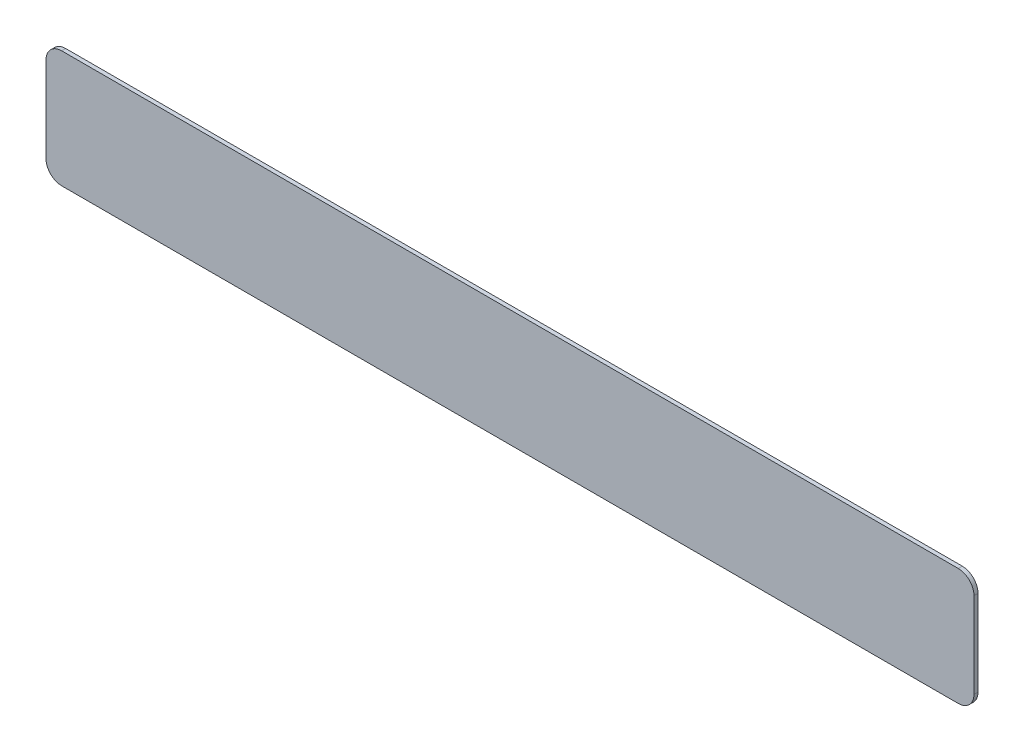
SolidWorks part; units mm, degrees
ref_plane "Front Plane" through (0, 0, 0) normal (0, 0, 1) x (1, 0, 0)
ref_plane "Top Plane" through (0, 0, 0) normal (0, 1, 0) x (1, 0, 0)
ref_plane "Right Plane" through (0, 0, 0) normal (1, 0, 0) x (0, 0, -1)
sketch "Sketch1" plane through (0, 0, 0) normal (0, 0, 1) x (1, 0, 0)
  line L1 (-35.65, 4.65) -> (35.65, 4.65)
  line L2 (-36.9, 3.4) -> (-36.9, -3.4)
  line L3 (-35.65, -4.65) -> (35.65, -4.65)
  line L4 (36.9, 3.4) -> (36.9, -3.4)
  line L5 (-36.9, 4.65) -> (36.9, -4.65) construction
  line L6 (-36.9, -4.65) -> (36.9, 4.65) construction
  arc A0 (-36.9, -3.4) -> (-35.65, -4.65) centre (-35.65, -3.4) ccw
  arc A1 (35.65, -4.65) -> (36.9, -3.4) centre (35.65, -3.4) ccw
  arc A2 (35.65, 4.65) -> (36.9, 3.4) centre (35.65, 3.4) cw
  arc A3 (-35.65, 4.65) -> (-36.9, 3.4) centre (-35.65, 3.4) ccw
  point P0 (0, 0)
  dimension "D1" = 9.3
  dimension "D2" = 1.25
  dimension "D3" = 73.8
extrude "Boss-Extrude1" add sketch "Sketch1" along normal blind 0.32
